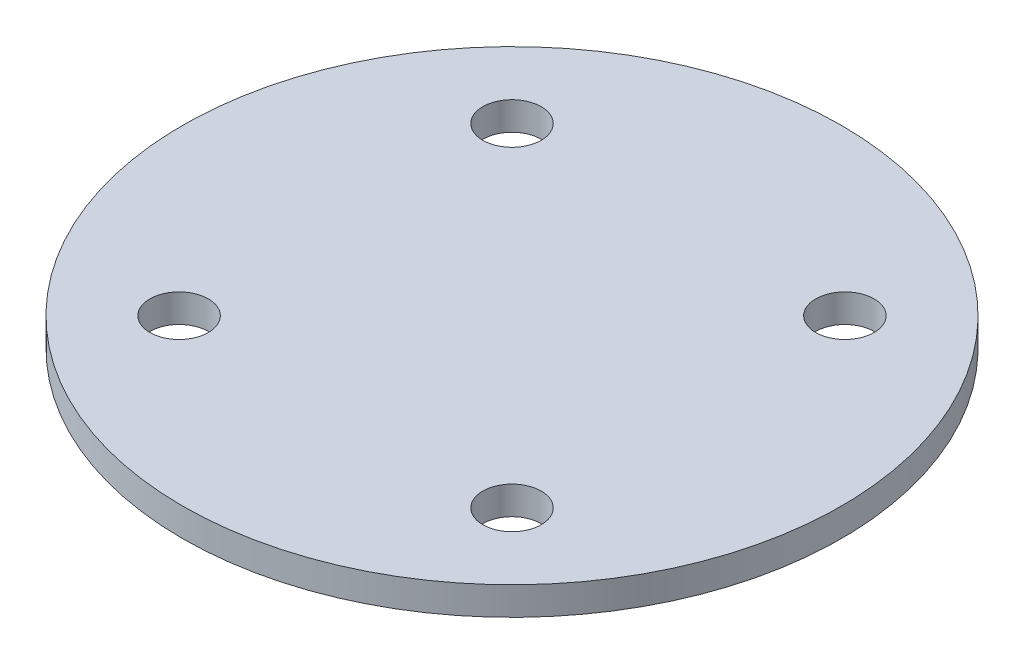
SolidWorks part; units mm, degrees
ref_plane "Front Plane" through (0, 0, 0) normal (0, 0, 1) x (1, 0, 0)
ref_plane "Top Plane" through (0, 0, 0) normal (0, 1, 0) x (1, 0, 0)
ref_plane "Right Plane" through (0, 0, 0) normal (1, 0, 0) x (0, 0, -1)
sketch "Sketch1" plane through (0, 0, 0) normal (0, 1, 0) x (1, 0, 0)
  circle A0 centre (0, 0) radius 35
  dimension "D1" = 70
extrude "Boss-Extrude1" add sketch "Sketch1" along normal blind 5
sketch "Sketch2" plane through (0, 5, 0) normal (0, 1, 0) x (1, 0, 0)
  circle A0 centre (-17.6777, 17.6777) radius 3.1
  circle A1 centre (17.6777, 17.6777) radius 3.1
  circle A2 centre (17.6777, -17.6777) radius 3.1
  circle A3 centre (-17.6777, -17.6777) radius 3.1
  dimension "D1" = 6.2
extrude "Cut-Extrude1" cut sketch "Sketch2" against normal through all
sketch "Sketch3" plane through (0, 5, 0) normal (0, 1, 0) x (1, 0, 0)
  line L0 (-6.17, 30.2) -> (6.17, 30.2) construction
  line L1 (-6.37, 19.6) -> (6.37, 19.6)
  line L2 (-6.37, 19.6) -> (-6.37, 30.4)
  line L3 (-6.37, 30.4) -> (6.37, 30.4)
  line L4 (6.37, 19.6) -> (6.37, 30.4)
  line L5 (-6.37, 19.6) -> (6.37, 30.4) construction
  line L6 (-6.37, 30.4) -> (6.37, 19.6) construction
  line L7 (-6.17, 19.8) -> (-6.17, 30.2) construction
  point P0 (0, 25)
  dimension "D1" = 0.2
  dimension "D2" = 0.2
extrude "Cut-Extrude2" [suppressed] cut sketch "Sketch3" against normal up to vertex
pattern_circular "CirPattern1" [suppressed] count 4 over 360
sketch "Sketch4" [suppressed] plane through (0, 0, -30.4) normal (0, 0, 1) x (1, 0, 0)
  line L4 (6.37, 5) -> (-6.37, 5)
  line L5 (-6.37, 5) -> (-6.37, 1)
  line L6 (-6.37, 1) -> (6.37, 1)
  line L7 (6.37, 1) -> (6.37, 5)
  line L8 (6.37, 5) -> (-6.37, 5)
  line L9 (-6.37, 5) -> (-6.37, 1)
  line L10 (-6.37, 1) -> (6.37, 1)
  line L11 (6.37, 1) -> (6.37, 5)
  dimension "D1" = 0
extrude "Cut-Extrude3" [suppressed] cut sketch "Sketch4" against normal through all
pattern_circular "CirPattern2" [suppressed] count 4 over 360
sketch "Sketch5" plane through (0, 0, 0) normal (0, -1, 0) x (1, 0, 0)
  circle A1 centre (0, 0) radius 35
  circle A2 centre (0, 0) radius 35
  dimension "D1" = 0
extrude "Cut-Extrude4" cut sketch "Sketch5" against normal offset from surface (2 mm away) 3 up to face at (-17.6777, 5, 20.7777)
